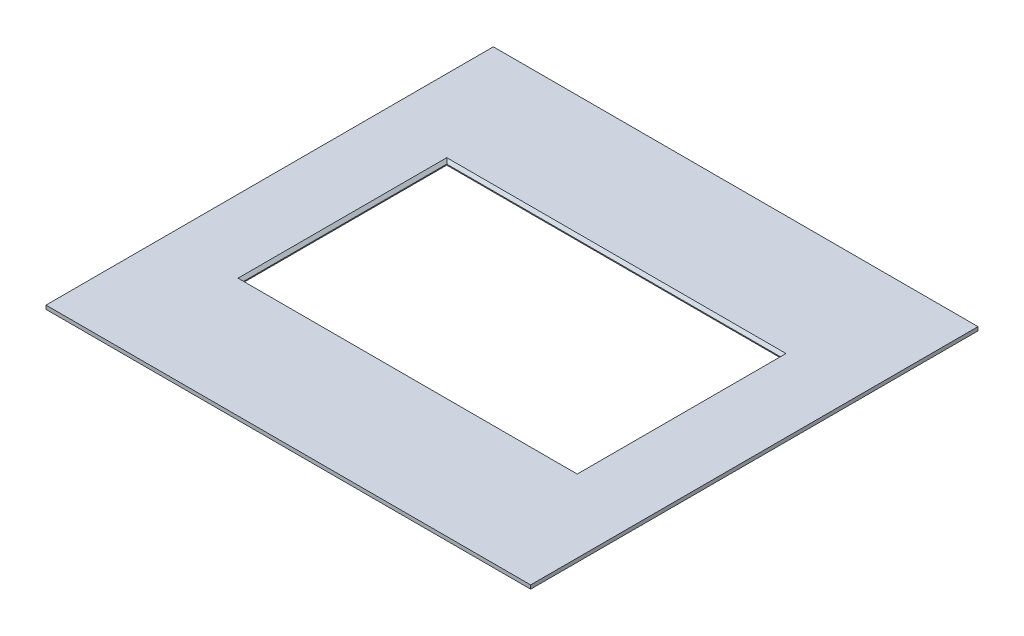
SolidWorks part; units mm, degrees
ref_plane "Front Plane" through (0, 0, 0) normal (0, 0, 1) x (1, 0, 0)
ref_plane "Top Plane" through (0, 0, 0) normal (0, 1, 0) x (1, 0, 0)
ref_plane "Right Plane" through (0, 0, 0) normal (1, 0, 0) x (0, 0, -1)
sketch "Sketch1" plane through (0, 0, 0) normal (0, 1, 0) x (1, 0, 0)
  line L1 (-65, 60) -> (65, 60)
  line L2 (-65, 60) -> (-65, -60)
  line L3 (-65, -60) -> (65, -60)
  line L4 (65, 60) -> (65, -60)
  line L5 (-65, 60) -> (65, -60) construction
  line L6 (-65, -60) -> (65, 60) construction
  line L7 (-44.75, 27.25) -> (44.75, 27.25)
  line L8 (-44.75, 27.25) -> (-44.75, -27.25)
  line L9 (-44.75, -27.25) -> (44.75, -27.25)
  line L10 (44.75, 27.25) -> (44.75, -27.25)
  line L11 (-44.75, 27.25) -> (44.75, -27.25) construction
  line L12 (-44.75, -27.25) -> (44.75, 27.25) construction
  point P0 (0, 0)
  point P6 (0, 0)
  dimension "D1" = 130
  dimension "D2" = 120
  dimension "D3" = 89.5
  dimension "D4" = 54.5
extrude "Boss-Extrude1" add sketch "Sketch1" along normal blind 1
chamfer "Chamfer1" distance 0.75 angle 45 4 edges at (0, 1, 27.25) (44.75, 1, 0) (0, 1, -27.25) (-44.75, 1, 0)
